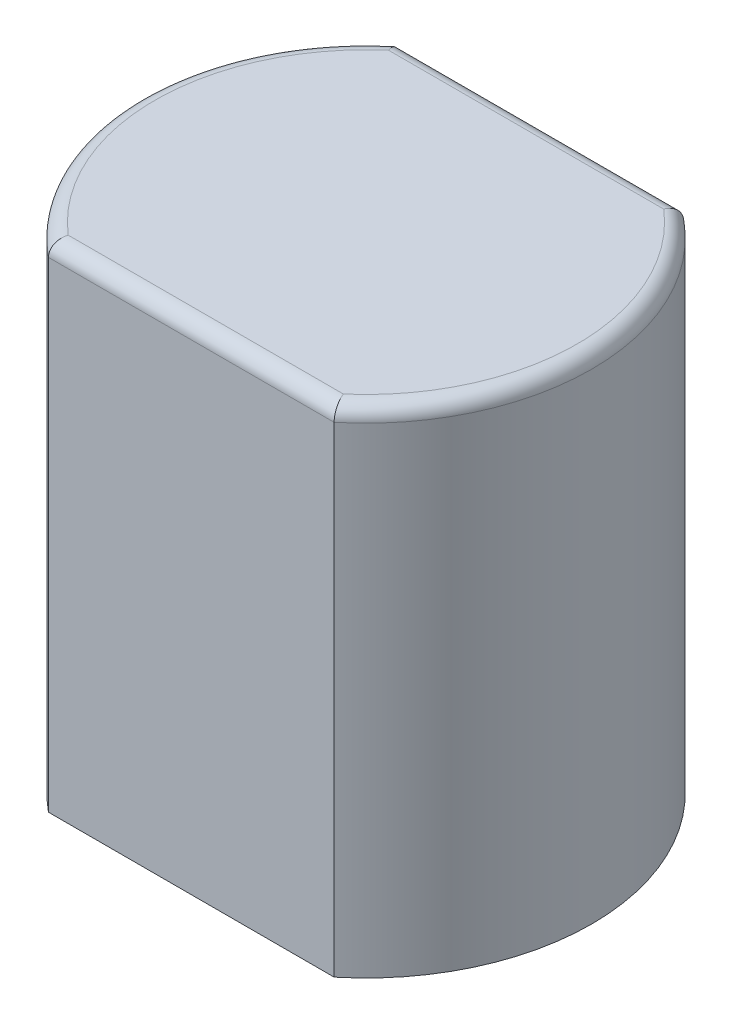
SolidWorks part; units mm, degrees
material "AISI 1020 Acero laminado en frío"
ref_plane "Alzado" through (0, 0, 0) normal (0, 0, 1) x (1, 0, 0)
ref_plane "Planta" through (0, 0, 0) normal (0, 1, 0) x (1, 0, 0)
ref_plane "Vista lateral" through (0, 0, 0) normal (1, 0, 0) x (0, 0, -1)
sketch "Croquis1" plane through (0, 0, 0) normal (0, 1, 0) x (1, 0, 0)
  line L1 (-4.9054, -6) -> (4.9054, -6)
  line L3 (-4.9054, 6) -> (4.9054, 6)
  line L5 (-4.9054, -6) -> (4.9054, 6) construction
  line L6 (-4.9054, 6) -> (4.9054, -6) construction
  arc A0 (-4.9054, 6) -> (-4.9054, -6) centre (0, 0) ccw
  arc A1 (4.9054, -6) -> (4.9054, 6) centre (0, 0) ccw
  dimension "D1" = 12
extrude "Saliente-Extruir1" add sketch "Croquis1" along normal blind 17
sketch "Croquis2" plane through (0, 0, 0) normal (0, -1, 0) x (1, 0, 0)
  line L0 (-4.9054, 6) -> (4.9054, 6)
  line L1 (5.5988, 5.3587) -> (4.8468, 4.7277)
  line L2 (4.9054, -6) -> (-4.9054, -6)
  line L8 (5.1722, 4.34) -> (5.4975, 3.9522) construction
  line L10 (4.8468, 4.7277) -> (5.4975, 3.9522)
  line L11 (6.2495, 4.5833) -> (5.4975, 3.9522)
  line L16 (-5.5988, -5.3587) -> (-4.8468, -4.7277)
  line L18 (-6.2495, -4.5833) -> (-5.4975, -3.9522)
  line L19 (-4.8468, -4.7277) -> (-5.4975, -3.9522)
  line L22 (-6.2495, 4.5833) -> (-5.4975, 3.9522)
  line L24 (-5.5988, 5.3587) -> (-4.8468, 4.7277)
  line L25 (-5.4975, 3.9522) -> (-4.8468, 4.7277)
  line L26 (6.2495, -4.5833) -> (5.4975, -3.9522)
  line L28 (5.5988, -5.3587) -> (4.8468, -4.7277)
  line L29 (5.4975, -3.9522) -> (4.8468, -4.7277)
  arc A0 (-4.9054, 6) -> (-5.5988, 5.3587) centre (0, 0) ccw
  arc A1 (4.9054, -6) -> (5.5988, -5.3587) centre (0, 0) ccw
  arc A2 (5.5988, 5.3587) -> (4.9054, 6) centre (0, 0) ccw
  arc A3 (6.2495, -4.5833) -> (6.2495, 4.5833) centre (0, 0) ccw
  arc A4 (-5.5988, -5.3587) -> (-4.9054, -6) centre (0, 0) ccw
  arc A5 (-6.2495, 4.5833) -> (-6.2495, -4.5833) centre (0, 0) ccw
  point P26 (0, 0)
  point P34 (0, 0)
  dimension "D1" = 2
  dimension "D2" = 2
fillet "Redondeo1" radius 0.5 4 edges at (-7.75, 17, 0) (0, 17, -6) (7.75, 17, 0) (0, 17, 6)
